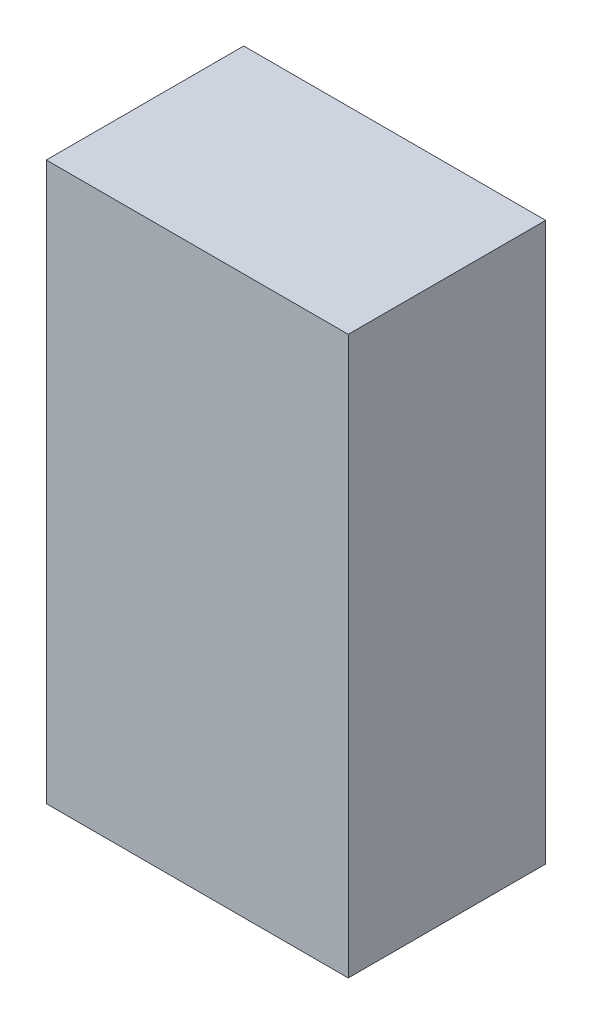
SolidWorks part; units mm, degrees
ref_plane "Front Plane" through (0, 0, 0) normal (0, 0, 1) x (1, 0, 0)
ref_plane "Top Plane" through (0, 0, 0) normal (0, 1, 0) x (1, 0, 0)
ref_plane "Right Plane" through (0, 0, 0) normal (1, 0, 0) x (0, 0, -1)
sketch "Sketch1" plane through (0, 0, 0) normal (0, 0, 1) x (1, 0, 0)
  line L1 (-13, -24) -> (13, -24)
  line L2 (-13, -24) -> (-13, 24)
  line L3 (-13, 24) -> (13, 24)
  line L4 (13, -24) -> (13, 24)
  line L5 (-13, -24) -> (13, 24) construction
  line L6 (-13, 24) -> (13, -24) construction
  point P0 (0, 0)
  dimension "D1" = 26
  dimension "D2" = 48
extrude "Boss-Extrude1" add sketch "Sketch1" along normal mid plane 17
